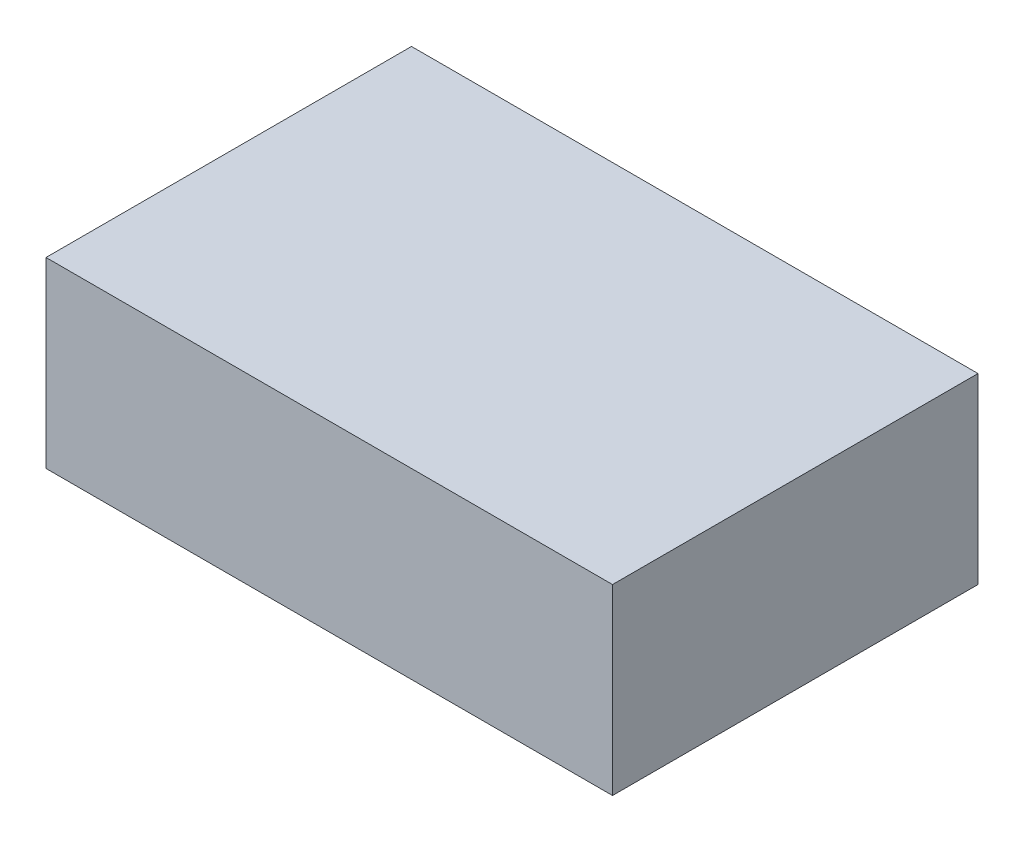
SolidWorks part; units mm, degrees
ref_plane "Front Plane" through (0, 0, 0) normal (0, 0, 1) x (1, 0, 0)
ref_plane "Top Plane" through (0, 0, 0) normal (0, 1, 0) x (1, 0, 0)
ref_plane "Right Plane" through (0, 0, 0) normal (1, 0, 0) x (0, 0, -1)
sketch "Sketch1" plane through (0, 0, 0) normal (0, 1, 0) x (1, 0, 0)
  line L1 (0, 0) -> (31, 0)
  line L2 (0, 0) -> (0, 20)
  line L3 (0, 20) -> (31, 20)
  line L4 (31, 0) -> (31, 20)
extrude "Boss-Extrude1" add sketch "Sketch1" along normal blind 10
